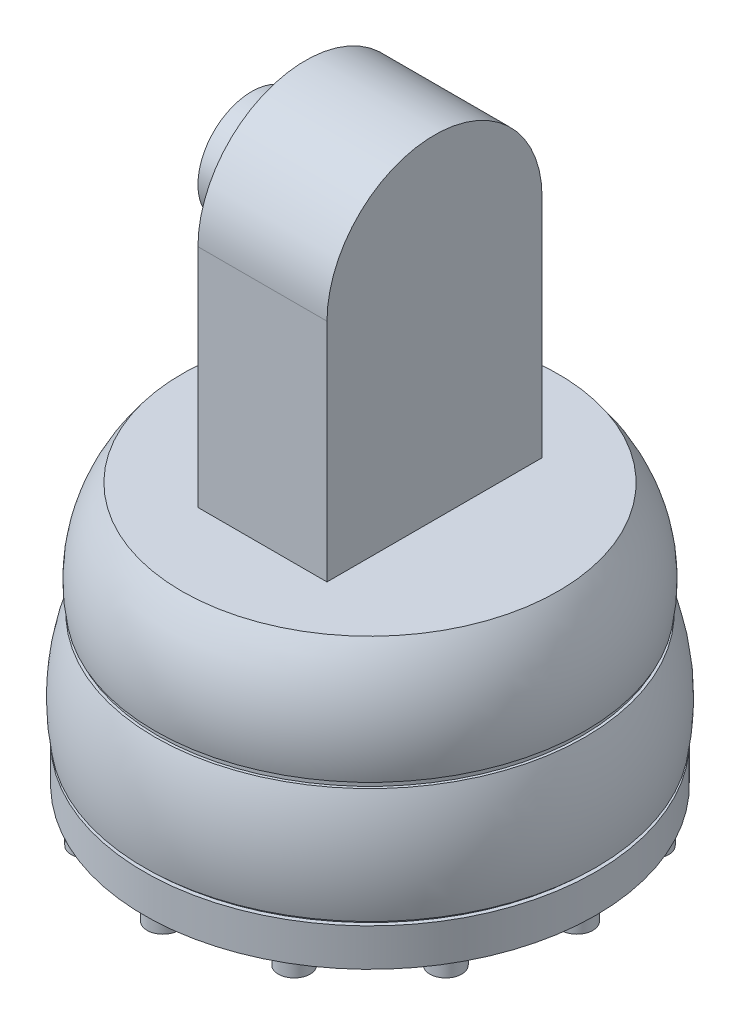
SolidWorks part; units mm, degrees
material "AISI 1045 Steel, cold drawn"
ref_plane "Front" through (0, 0, 0) normal (0, 0, 1) x (1, 0, 0)
ref_plane "Top" through (0, 0, 0) normal (0, 1, 0) x (1, 0, 0)
ref_plane "Right" through (0, 0, 0) normal (1, 0, 0) x (0, 0, -1)
sketch "Sketch1" plane through (0, 0, 0) normal (0, 0, 1) x (1, 0, 0)
  line L0 (0, 0) -> (-35, 0)
  line L1 (0, 0) -> (0, -20)
  line L2 (0, -20) -> (-40, -20)
  arc A0 (-35, 0) -> (-40, -20) centre (-15.404, -15.524) ccw
  dimension "D4" = 25
  dimension "D1" = 35
  dimension "D2" = 20
  dimension "D3" = 40
revolve "Revolve1" add sketch "Sketch1" angle 360 about L1
sketch "Sketch2" plane through (0, -20, 0) normal (0, -1, 0) x (1, 0, 0)
  circle A0 centre (0, 0) radius 39.5
  dimension "D1" = 79
extrude "Boss-Extrude1" add sketch "Sketch2" along normal blind 1
sketch "Sketch3" plane through (0, 0, 0) normal (0, 0, 1) x (1, 0, 0)
  line L0 (0, -21) -> (-40, -21)
  line L1 (-39.5, -21) -> (39.5, -21) construction
  line L2 (0, -21) -> (0, -41)
  line L3 (0, -41) -> (-42, -41)
  arc A0 (-40, -21) -> (-42, -41) centre (-5.5677, -34.5432) ccw
  dimension "D4" = 37
  dimension "D1" = 40
  dimension "D2" = 20
  dimension "D3" = 42
revolve "Revolve2" add sketch "Sketch3" angle 360 about L2
sketch "Sketch4" plane through (0, -41, 0) normal (0, -1, 0) x (1, 0, 0)
  circle A0 centre (0, 0) radius 41.25
  dimension "D1" = 82.5
extrude "Boss-Extrude2" add sketch "Sketch4" along normal blind 0.7
sketch "Sketch5" plane through (0, -41.7, 0) normal (0, -1, 0) x (1, 0, 0)
  circle A0 centre (0, 0) radius 42
  dimension "D1" = 84
extrude "Boss-Extrude3" add sketch "Sketch5" along normal blind 7
sketch "Sketch6" plane through (0, -48.7, 0) normal (0, -1, 0) x (1, 0, 0)
  circle A0 centre (0, 0) radius 35
  dimension "D1" = 70
extrude "Boss-Extrude4" add sketch "Sketch6" along normal blind 3
sketch "Sketch7" plane through (0, -48.7, 0) normal (0, -1, 0) x (1, 0, 0)
  line L0 (35, 0) -> (42, 0) construction
  circle A0 centre (0, 0) radius 35 construction
  circle A1 centre (0, 0) radius 35 construction
  circle A2 centre (0, 0) radius 42 construction
  circle A3 centre (38.5, 0) radius 2.9593
extrude "Boss-Extrude5" add sketch "Sketch7" along normal blind 2.7
sketch "Sketch8" plane through (0, -51.4, 0) normal (0, -1, 0) x (1, 0, 0)
  circle A3 centre (38.5, 0) radius 2.2593
  circle A4 centre (38.5, 0) radius 2.2593
  dimension "D1" = 0.7
extrude "Cut-Extrude1" cut sketch "Sketch8" against normal blind 0.5
pattern_circular "CirPattern1" count 12 over 360 about axis through (0, 0, 0) along (0, 1, 0) of "Boss-Extrude5", "Cut-Extrude1"
sketch "Sketch9" plane through (0, 0, 0) normal (0, 1, 0) x (1, 0, 0)
  line L1 (12, -20) -> (-12, -20)
  line L2 (12, -20) -> (12, 20)
  line L3 (12, 20) -> (-12, 20)
  line L4 (-12, -20) -> (-12, 20)
  line L5 (12, -20) -> (-12, 20) construction
  line L6 (12, 20) -> (-12, -20) construction
  point P0 (0, 0)
  dimension "D1" = 24
  dimension "D2" = 40
extrude "Boss-Extrude6" add sketch "Sketch9" along normal blind 42
sketch "Sketch10" plane through (12, 0, 0) normal (1, 0, 0) x (0, 0, -1)
  line L0 (-20, 42) -> (20, 42) construction
  line L1 (-20, 42) -> (20, 42)
  arc A0 (20, 42) -> (-20, 42) centre (0, 42) ccw
extrude "Boss-Extrude7" add sketch "Sketch10" against normal up to surface (24 mm away) up to face at (-12, 21, 0)
sketch "Sketch13" plane through (-12, 0, 0) normal (-1, 0, 0) x (0, 0, 1)
  circle A0 centre (0, 42) radius 10
  dimension "D1" = 20
extrude "Boss-Extrude10" add sketch "Sketch13" along normal blind 10
sketch "Sketch14" plane through (0, -51.7, 0) normal (0, -1, 0) x (1, 0, 0)
  circle A0 centre (0, 0) radius 10
  dimension "D1" = 20
extrude "Boss-Extrude11" add sketch "Sketch14" along normal blind 10
